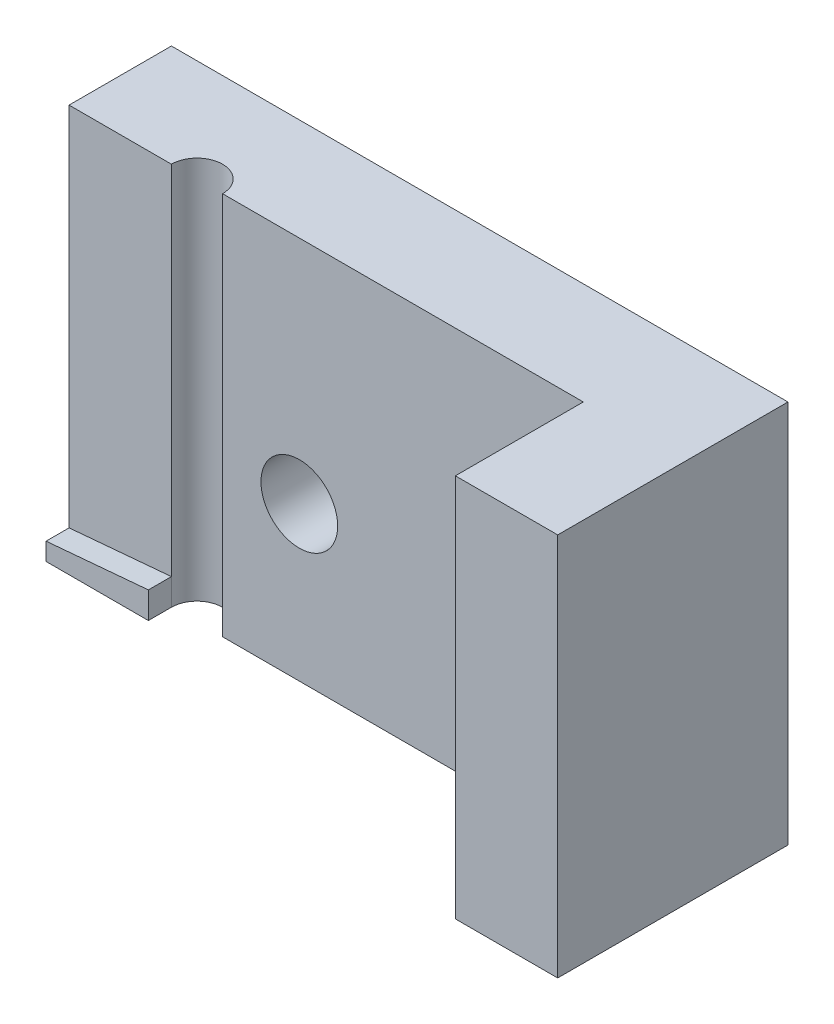
SolidWorks part; units mm, degrees
ref_plane "前视基准面" through (0, 0, 0) normal (0, 0, 1) x (1, 0, 0)
ref_plane "上视基准面" through (0, 0, 0) normal (0, 1, 0) x (1, 0, 0)
ref_plane "右视基准面" through (0, 0, 0) normal (1, 0, 0) x (0, 0, -1)
sketch "草图1" plane through (0, 0, 0) normal (0, 0, 1) x (1, 0, 0)
  line L1 (-12.05, 7.5) -> (12.05, 7.5)
  line L2 (-12.05, 7.5) -> (-12.05, -7.5)
  line L3 (-12.05, -7.5) -> (12.05, -7.5)
  line L4 (12.05, 7.5) -> (12.05, -7.5)
  line L5 (-12.05, 7.5) -> (12.05, -7.5) construction
  line L6 (-12.05, -7.5) -> (12.05, 7.5) construction
  point P0 (0, 0)
  dimension "D1" = 24.1
  dimension "D2" = 15
extrude "凸台-拉伸1" add sketch "草图1" against normal blind 4
sketch "草图2" plane through (0, -7.5, 0) normal (0, -1, 0) x (1, 0, 0)
  line L0 (-12.05, 0) -> (12.05, 0) construction
  line L1 (-8.05, 0) -> (-6.05, 0)
  arc A0 (-6.05, 0) -> (-8.05, 0) centre (-7.05, 0) cw
  dimension "D1" = 1
  dimension "D2" = 5
extrude "切除-拉伸1" cut sketch "草图2" against normal up to surface (15 mm away) up to face at (0, 7.5, -2)
sketch "草图3" plane through (0, 0, 0) normal (0, 0, 1) x (1, 0, 0)
  line L0 (-8.05, 7.5) -> (-8.05, -7.5) construction
  line L1 (-8.05, -6.4622) -> (-8.05, -7.5)
  line L2 (-8.05, -6.4622) -> (-12.05, -6.8121)
  line L3 (-8.05, -6.4622) -> (-16.9628, -7.2419) construction
  line L4 (-12.05, 7.5) -> (-12.05, -7.5) construction
  line L5 (-12.05, -6.8121) -> (-12.05, -7.5)
  line L6 (-12.05, -7.5) -> (-8.05, -7.5)
extrude "凸台-拉伸2" add sketch "草图3" along normal blind 0.9
sketch "草图4" plane through (0, 0, 0) normal (0, 0, 1) x (1, 0, 0)
  line L0 (-12.05, -7.5) -> (-3.05, -7.5) construction
  line L1 (-6.05, -7.5) -> (12.05, -7.5) construction
  line L2 (-3.05, -7.5) -> (-3.05, -1.5) construction
  circle A0 centre (-3.05, -1.5) radius 1.5
  dimension "D3" = 3
  dimension "D1" = 9
  dimension "D2" = 6
extrude "切除-拉伸2" cut sketch "草图4" against normal up to surface (4 mm away) up to face at (0, 0, -4)
sketch "草图5" plane through (0, 0, 0) normal (0, 0, 1) x (1, 0, 0)
  line L0 (-6.05, -7.5) -> (12.05, -7.5) construction
  line L1 (12.05, 7.5) -> (8.05, 7.5)
  line L2 (12.05, 7.5) -> (12.05, -7.5)
  line L3 (12.05, -7.5) -> (8.05, -7.5)
  line L4 (8.05, 7.5) -> (8.05, -7.5)
  dimension "D1" = 4
extrude "凸台-拉伸3" add sketch "草图5" along normal blind 5
